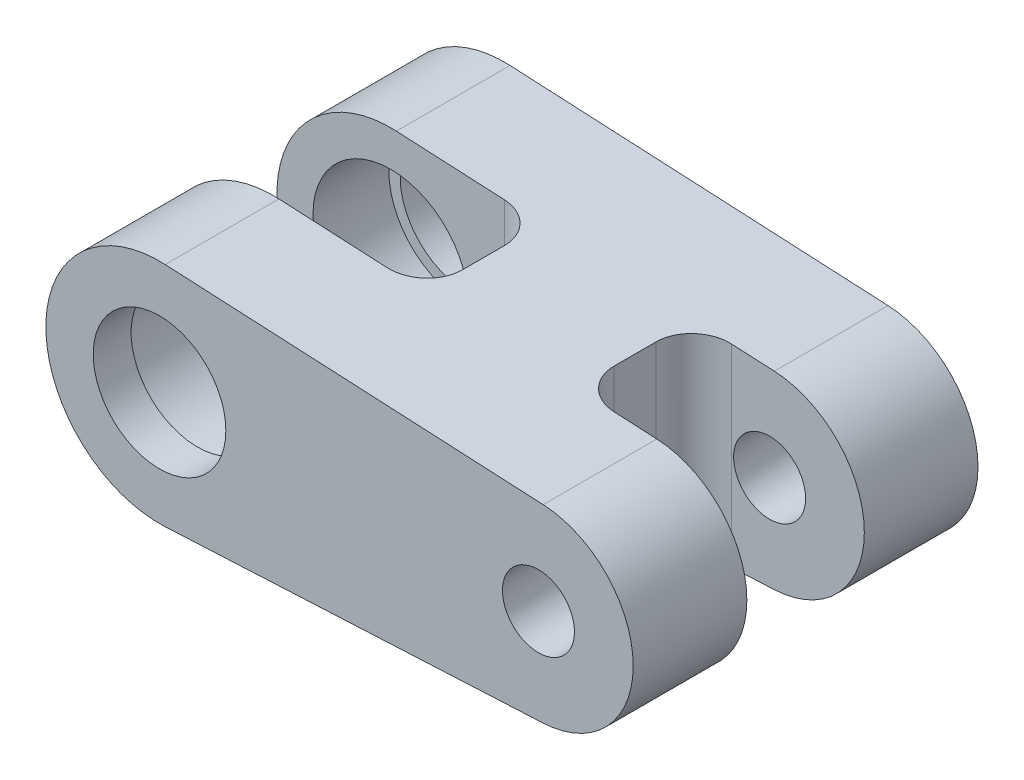
SolidWorks part; units mm, degrees
ref_plane "正面" through (0, 0, 0) normal (0, 0, 1) x (1, 0, 0)
ref_plane "平面" through (0, 0, 0) normal (0, 1, 0) x (1, 0, 0)
ref_plane "右側面" through (0, 0, 0) normal (1, 0, 0) x (0, 0, -1)
sketch "ｽｹｯﾁ1" plane through (0, 0, 0) normal (0, 0, 1) x (1, 0, 0)
  line L0 (0.25, 4.9937) -> (-19.7, 5.9925)
  line L1 (0.25, -4.9937) -> (-19.7, -5.9925)
  arc A0 (0.25, 4.9937) -> (0.25, -4.9937) centre (0, 0) cw
  arc A1 (-19.7, 5.9925) -> (-19.7, -5.9925) centre (-20, 0) ccw
  dimension "D1" = 5
  dimension "D2" = 6
  dimension "D3" = 20
extrude "ﾎﾞｽ - 押し出し1" add sketch "ｽｹｯﾁ1" along normal blind 6 from offset 9.1 offset against normal yes
sketch "ｽｹｯﾁ4" plane through (0, 0, -3.1) normal (0, 0, 1) x (1, 0, 0)
  circle A0 centre (-20, 0) radius 4.1
  arc A1 (-19.7, 5.9925) -> (-19.7, -5.9925) centre (-20, 0) ccw construction
  dimension "D1" = 8.2
extrude "ｶｯﾄ - 押し出し3" cut sketch "ｽｹｯﾁ4" against normal blind 4
sketch "ｽｹｯﾁ5" plane through (0, 0, -3.1) normal (0, 0, 1) x (1, 0, 0)
  circle A0 centre (-20, 0) radius 3.5
  dimension "D1" = 7
extrude "ｶｯﾄ - 押し出し5" cut sketch "ｽｹｯﾁ5" against normal through all
sketch "ｽｹｯﾁ6" plane through (0, 0, -3.1) normal (0, 0, 1) x (1, 0, 0)
  circle A0 centre (0, 0) radius 1.9
  dimension "D1" = 3.8
extrude "ｶｯﾄ - 押し出し6" cut sketch "ｽｹｯﾁ6" against normal blind 10
sketch "ｽｹｯﾁ7" plane through (0, 0, -3.1) normal (0, 0, 1) x (1, 0, 0)
  line L0 (0.25, 4.9937) -> (-19.7, 5.9925) construction
  line L1 (-4, 5.2065) -> (-12, 5.607)
  line L2 (-4, 5.2065) -> (-4, -5.2065)
  line L3 (-4, -5.2065) -> (-12, -5.607)
  line L4 (-12, 5.607) -> (-12, -5.607)
  line L5 (-19.7, -5.9925) -> (0.25, -4.9937) construction
  circle A0 centre (-20, 0) radius 4.1 construction
  circle A1 centre (0, 0) radius 1.9 construction
  point P12 (-12, 6.0171)
  point P13 (0, 0)
  dimension "D1" = 8
  dimension "D2" = 4
extrude "ﾎﾞｽ - 押し出し2" add sketch "ｽｹｯﾁ7" along normal up to surface (3.1 mm away) up to plane "正面"
mirror "ﾐﾗｰ3" about plane through (0, 0, 0) normal (0, 0, 1) of "ﾎﾞｽ - 押し出し2", "ｶｯﾄ - 押し出し6", "ｶｯﾄ - 押し出し5", "ｶｯﾄ - 押し出し3", "ﾎﾞｽ - 押し出し1"
fillet "ﾌｨﾚｯﾄ1" radius 2 4 edges at (-12, 0, 3.1) (-12, 0, -3.1) (-4, 0, 3.1) (-4, 0, -3.1)
